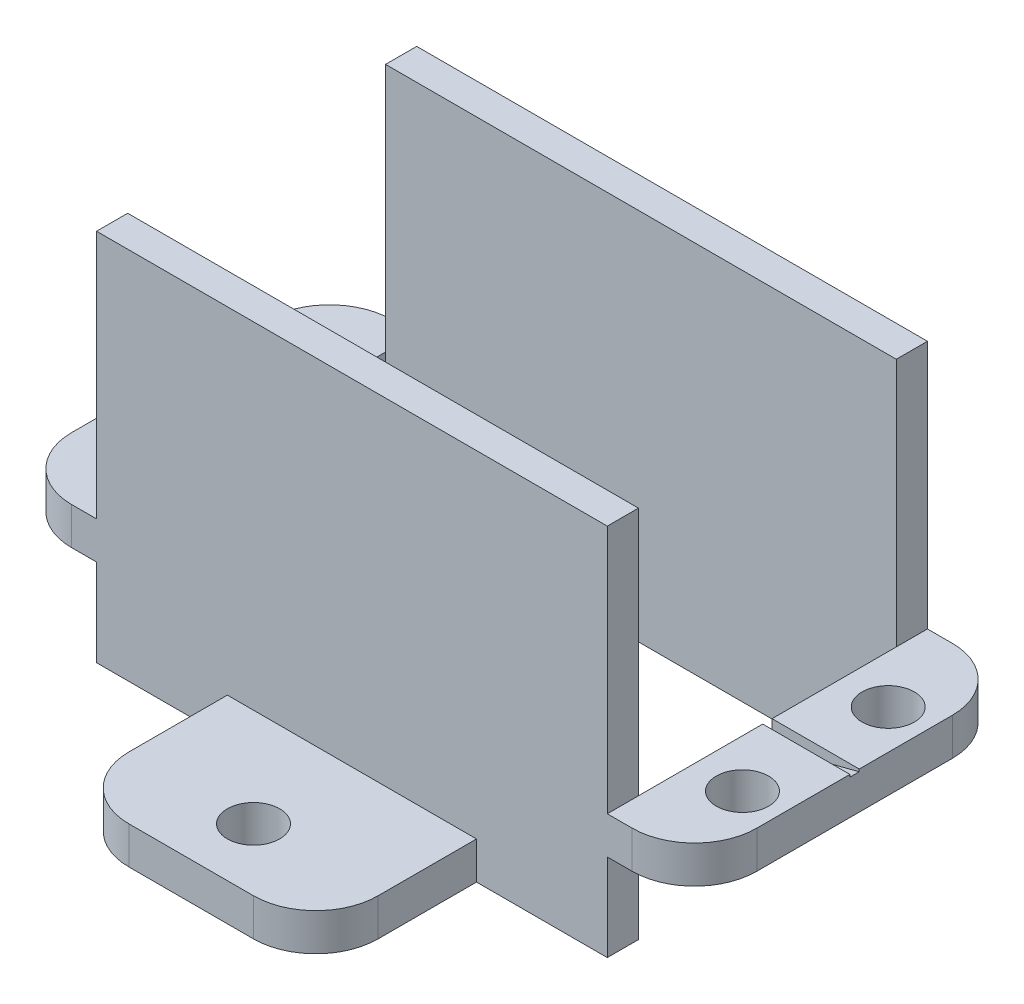
SolidWorks part; units mm, degrees
material "PBT General Purpose"
ref_plane "Front Plane" through (0, 0, 0) normal (0, 0, 1) x (1, 0, 0)
ref_plane "Top Plane" through (0, 0, 0) normal (0, 1, 0) x (1, 0, 0)
ref_plane "Right Plane" through (0, 0, 0) normal (1, 0, 0) x (0, 0, -1)
sketch "Sketch1" plane through (0, 0, 0) normal (0, 1, 0) x (1, 0, 0)
  line L1 (27.5, -12.85) -> (-27.5, -12.85)
  line L2 (27.5, -12.85) -> (27.5, 12.85)
  line L3 (27.5, 12.85) -> (-27.5, 12.85)
  line L4 (-27.5, -12.85) -> (-27.5, 12.85)
  line L5 (27.5, -12.85) -> (-27.5, 12.85) construction
  line L6 (27.5, 12.85) -> (-27.5, -12.85) construction
  point P0 (0, 0)
  dimension "D1" = 25.7
  dimension "D2" = 55
extrude "Boss-Extrude1" add sketch "Sketch1" along normal blind 3
sketch "Sketch2" plane through (0, 3, 0) normal (0, 1, 0) x (1, 0, 0)
  line L1 (20.5, -10.35) -> (-20.5, -10.35)
  line L2 (20.5, -10.35) -> (20.5, 10.35)
  line L3 (20.5, 10.35) -> (-20.5, 10.35)
  line L4 (-20.5, -10.35) -> (-20.5, 10.35)
  line L5 (20.5, -10.35) -> (-20.5, 10.35) construction
  line L6 (20.5, 10.35) -> (-20.5, -10.35) construction
  point P0 (0, 0)
  dimension "D1" = 20.7
  dimension "D2" = 41
extrude "Cut-Extrude1" cut sketch "Sketch2" against normal through all
sketch "Sketch3" plane through (0, 3, 0) normal (0, 1, 0) x (1, 0, 0)
  line L0 (27.5, 12.85) -> (-27.5, 12.85) construction
  line L1 (20.5, -10.35) -> (20.5, 10.35) construction
  circle A0 centre (24.35, 5.85) radius 2.1
  circle A1 centre (24.35, -5.85) radius 2.1
  dimension "D1" = 11.7
  dimension "D2" = 7
  dimension "D3" = 3.85
  dimension "D4" = 4.2
extrude "Cut-Extrude2" cut sketch "Sketch3" against normal through all
mirror "Mirror1" about plane through (0, 0, 0) normal (1, 0, 0) of "Cut-Extrude2"
sketch "Sketch4" plane through (0, 3, 0) normal (0, 1, 0) x (1, 0, 0)
  line L0 (-20.5, 10.35) -> (-20.5, 12.85)
  line L1 (27.5, 12.85) -> (-27.5, 12.85) construction
  line L2 (20.5, 10.35) -> (20.5, 12.85)
  line L3 (20.5, 12.85) -> (-20.5, 12.85)
  line L4 (20.5, 10.35) -> (-20.5, 10.35) construction
  line L5 (20.5, 10.35) -> (-20.5, 10.35)
  line L6 (-20.5, -10.35) -> (-20.5, -12.85)
  line L7 (-27.5, -12.85) -> (27.5, -12.85) construction
  line L8 (20.5, -10.35) -> (20.5, -12.85)
  line L9 (-20.5, -10.35) -> (20.5, -10.35) construction
  line L10 (-20.5, -10.35) -> (20.5, -10.35)
  line L11 (-20.5, -12.85) -> (20.5, -12.85)
extrude "Boss-Extrude2" add sketch "Sketch4" along normal blind 20
sketch "Sketch5" plane through (0, 0, 0) normal (0, 0, 1) x (1, 0, 0)
  line L0 (20.5, 1) -> (20.5, 3)
  line L1 (20.5, 23) -> (20.5, 3) construction
  line L2 (20.5, 3) -> (28.246, 3)
  line L3 (28.246, 3) -> (20.5, 1)
  dimension "D1" = 2
  dimension "D2" = 8
extrude "Cut-Extrude3" cut sketch "Sketch5" against normal mid plane 0.75
mirror "Mirror2" about plane through (0, 0, 0) normal (1, 0, 0) of "Cut-Extrude3"
fillet "Fillet1" radius 5 4 edges at (-27.5, 1.5, 12.85) (-27.5, 1.5, -12.85) (27.5, 1.5, -12.85) (27.5, 1.5, 12.85)
sketch "Sketch6" plane through (0, 0, 0) normal (0, -1, 0) x (1, 0, 0)
  line L1 (-20.5, 10.35) -> (20.5, 10.35)
  line L2 (-20.5, 10.35) -> (-20.5, 12.85)
  line L3 (-20.5, 12.85) -> (20.5, 12.85)
  line L4 (20.5, 10.35) -> (20.5, 12.85)
  line L5 (-20.5, -10.35) -> (20.5, -10.35)
  line L6 (-20.5, -10.35) -> (-20.5, -12.85)
  line L7 (-20.5, -12.85) -> (20.5, -12.85)
  line L8 (20.5, -10.35) -> (20.5, -12.85)
extrude "Boss-Extrude3" add sketch "Sketch6" along normal blind 7
sketch "Sketch7" plane through (0, 0, 12.85) normal (0, 0, 1) x (1, 0, 0)
  line L0 (20.5, -7) -> (-20.5, -7) construction
  line L1 (-10, -7) -> (10, -7)
  line L2 (-10, -7) -> (-10, -4)
  line L3 (-10, -4) -> (10, -4)
  line L4 (10, -7) -> (10, -4)
  point P6 (0, -4)
  dimension "D1" = 20
  dimension "D2" = 3
extrude "Boss-Extrude4" add sketch "Sketch7" along normal blind 12.9
sketch "Sketch8" plane through (0, -4, 0) normal (0, 1, 0) x (1, 0, 0)
  line L0 (-10, -25.75) -> (-10, -12.85) construction
  line L2 (10, -12.85) -> (-10, -12.85) construction
  circle A0 centre (0, -20.75) radius 2.1
  dimension "D1" = 4.2
  dimension "D2" = 10
  dimension "D3" = 7.9
extrude "Cut-Extrude4" cut sketch "Sketch8" against normal through all
fillet "Fillet2" radius 5 2 edges at (-10, -5.5, 25.75) (10, -5.5, 25.75)
mirror "Mirror5" about plane through (0, 0, 0) normal (0, 0, 1) of "Boss-Extrude4", "Fillet2", "Cut-Extrude4"
sketch "Sketch9" plane through (0, -7, 0) normal (0, -1, 0) x (1, 0, 0)
  point P0 (0, 20.75)
  point P1 (0, -20.75)
